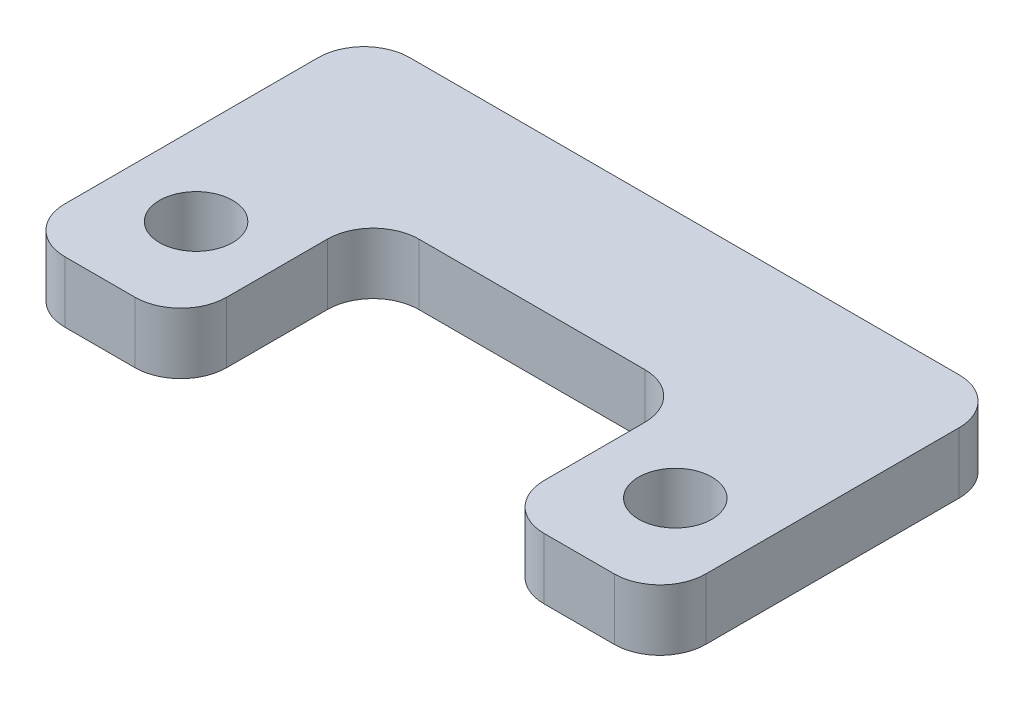
SolidWorks part; units mm, degrees
ref_plane "Front Plane" through (0, 0, 0) normal (0, 0, 1) x (1, 0, 0)
ref_plane "Top Plane" through (0, 0, 0) normal (0, 1, 0) x (1, 0, 0)
ref_plane "Right Plane" through (0, 0, 0) normal (1, 0, 0) x (0, 0, -1)
sketch "Sketch1" plane through (0, 0, 0) normal (0, 1, 0) x (1, 0, 0)
  line L0 (-5.2, -2.5) -> (-10.5, -8.8) construction
  line L1 (-10.5, 2.5) -> (10.5, 2.5)
  line L2 (-10.5, 2.5) -> (-10.5, -2.5)
  line L3 (-5.2, -2.5) -> (5.2, -2.5)
  line L4 (10.5, 2.5) -> (10.5, -2.5)
  line L5 (-10.5, 2.5) -> (10.5, -2.5) construction
  line L6 (-10.5, -2.5) -> (10.5, 2.5) construction
  line L8 (-10.5, -2.5) -> (-10.5, -8.8)
  line L9 (-10.5, -8.8) -> (-5.2, -8.8)
  line L10 (-5.2, -2.5) -> (-5.2, -8.8)
  line L12 (10.5, -2.5) -> (10.5, -8.8)
  line L13 (10.5, -8.8) -> (5.2, -8.8)
  line L14 (5.2, -2.5) -> (5.2, -8.8)
  line L15 (5.2, -2.5) -> (10.5, -8.8) construction
  line L16 (-7.85, -5.65) -> (7.85, -5.65) construction
  line L17 (5.2, -2.5) -> (10.5, -2.5) construction
  point P0 (0, 0)
  dimension "D2" = 5.3
  dimension "D3" = 6.3
  dimension "D4" = 6.3
  dimension "D5" = 5.3
  dimension "D6" = 15.7
  dimension "D7" = 5
extrude "Boss-Extrude1" add sketch "Sketch1" along normal blind 2
sketch "Sketch2" plane through (0, 2, 0) normal (0, 1, 0) x (1, 0, 0)
  line L0 (-5.2, -2.5) -> (-10.5, -8.8)
  line L1 (5.2, -2.5) -> (10.5, -8.8)
hole_wizard "M2 Clearance Hole1" positions "Sketch5" profile "Sketch6" hole size "M2" standard "BSI" end condition through all
sketch "Sketch5" plane through (0, 2, 0) normal (0, 1, 0) x (1, 0, 0)
  line L0 (-5.2, -2.5) -> (-10.5, -8.8) construction
  line L1 (5.2, -2.5) -> (10.5, -8.8) construction
  point P0 (-7.85, -5.65)
  point P4 (7.85, -5.65)
sketch "Sketch6" plane through (-7.85, 2, 5.65) normal (1, 0, 0) x (0, 0, 1)
  line L0 (0, 0) -> (0, 2)
  line L1 (0, 2) -> (1.2, 2)
  line L2 (1.2, 2) -> (1.2, 0)
  line L5 (1.2, 0) -> (0, 0)
  line L11 (0, -6.35) -> (0, 107.95) construction
  dimension "Thru Hole Dia." = 2.4
  dimension "Thru Hole Depth" = 2
fillet "Fillet1" radius 1.5 8 edges at (10.5, 1, -2.5) (10.5, 1, 8.8) (5.2, 1, 8.8) (-5.2, 1, 2.5) (5.2, 1, 2.5) (-5.2, 1, 8.8) (-10.5, 1, 8.8) (-10.5, 1, -2.5)
